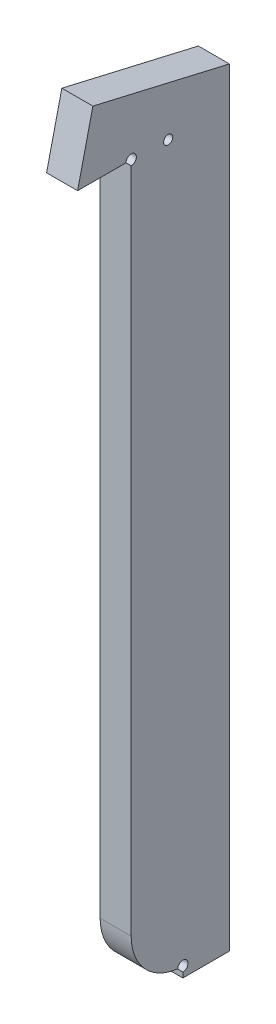
SolidWorks part; units mm, degrees
material "MDF"
ref_plane "Front Plane" through (0, 0, 0) normal (0, 0, 1) x (1, 0, 0)
ref_plane "Top Plane" through (0, 0, 0) normal (0, 1, 0) x (1, 0, 0)
ref_plane "Right Plane" through (0, 0, 0) normal (1, 0, 0) x (0, 0, -1)
sketch "Sketch1" plane through (0, 0, 0) normal (0, 0, 1) x (1, 0, 0)
  line L0 (-181.9836, -463.55) -> (-104.775, -463.55) construction
  line L1 (-228.0888, 0) -> (-209.0388, 0)
  line L2 (-228.0888, 0) -> (-228.0888, -450.85)
  line L3 (-228.0888, -450.85) -> (-209.0388, -450.85)
  line L4 (-209.0388, 0) -> (-209.0388, -450.85)
  dimension "D1" = 19.05
  dimension "D2" = 12.7
extrude "Boss-Extrude1" add sketch "Sketch1" along normal blind 66.675
fillet "Fillet4" radius 38.1 1 edges at (-218.5638, -450.85, 66.675)
sketch "Sketch4" plane through (-228.0888, 0, 0) normal (-1, 0, 0) x (0, 0, 1)
  line L1 (66.675, 0) -> (66.675, -412.75) construction
  line L3 (66.675, 0) -> (66.675, -412.75)
  line L4 (60.325, 0) -> (60.325, -412.75)
  line L5 (28.575, -450.85) -> (28.575, -444.5)
  line L6 (66.675, 0) -> (60.325, 0)
  arc A1 (28.575, -450.85) -> (66.675, -412.75) centre (28.575, -412.75) ccw construction
  arc A3 (28.575, -450.85) -> (66.675, -412.75) centre (28.575, -412.75) ccw
  arc A4 (28.575, -444.5) -> (60.325, -412.75) centre (28.575, -412.75) ccw
  dimension "D1" = 6.35
extrude "Cut-Extrude1" cut sketch "Sketch4" against normal up to next
sketch "Sketch7" plane through (-228.0888, 0, 0) normal (-1, 0, 0) x (0, 0, 1)
  line L0 (0, 0) -> (60.325, 0)
  line L1 (60.325, 0) -> (60.325, 34.8446)
  line L2 (495.3358, 135.9439) -> (380.7162, 109.3055) construction
  line L3 (60.325, 34.8446) -> (0, 20.8246)
  line L4 (0, 20.8246) -> (0, 0)
extrude "Boss-Extrude2" add sketch "Sketch7" against normal through all
sketch "Sketch8" plane through (-228.0888, 0, 0) normal (-1, 0, 0) x (0, 0, 1)
  line L0 (60.325, 34.8446) -> (83.8286, 40.3069)
  line L1 (83.8286, 40.3069) -> (93.1962, 0)
  line L2 (93.1962, 0) -> (60.325, 0)
  line L3 (60.325, 34.8446) -> (0, 20.8246) construction
  line L4 (60.325, 0) -> (60.325, 34.8446)
  dimension "D1" = 90
  dimension "D2" = 24.13
extrude "Boss-Extrude3" add sketch "Sketch8" against normal through all
chamfer "Chamfer1" [suppressed] distance 12.7 angle 45
hole_wizard "1/4 (0.25) Diameter Hole1" positions "Sketch5" profile "Sketch6" hole size "1/4" standard "ANSI Inch" end condition up to next
sketch "Sketch5" plane through (-228.0888, 0, 0) normal (-1, 0, 0) x (0, 0, 1)
  point P0 (28.575, -444.5)
  point P3 (60.325, 0)
sketch "Sketch6" plane through (-228.0888, -444.5, 28.575) normal (0, 1, 0) x (0, 0, 1)
  line L0 (0, 0) -> (0, 19.05)
  line L1 (0, 19.05) -> (3.175, 19.05)
  line L2 (3.175, 19.05) -> (3.175, 0)
  line L5 (3.175, 0) -> (0, 0)
  line L11 (0, -6.35) -> (0, 107.95) construction
  dimension "Thru Hole Dia." = 6.35
  dimension "Thru Hole Depth" = 19.05
hole_wizard "#10 Clearance Hole with 1.0 x .25 CB" positions "Sketch10" profile "Sketch11" legacy end condition up to next
sketch "Sketch10" plane through (-228.0888, 0, 0) normal (-1, 0, 0) x (0, 0, 1)
  point P0 (37.5801, -0.6606)
sketch "Sketch11" plane through (-228.0888, -0.6606, 37.5801) normal (0, 1, 0) x (0, 0, 1)
  line L0 (0, 0) -> (0, 19.05)
  line L1 (0, 19.05) -> (2.8067, 19.05)
  line L2 (2.8067, 19.05) -> (2.8067, 6.35)
  line L3 (2.8067, 6.35) -> (6.35, 6.35)
  line L4 (6.35, 6.35) -> (6.35, 0)
  line L5 (6.35, 0) -> (0, 0)
  line L6 (0, 110) -> (0, -10) construction
  dimension "Diameter" = 5.6134
  dimension "Depth" = 19.05
  dimension "C-Bore Diameter" = 12.7
  dimension "C-Bore Depth" = 6.35
